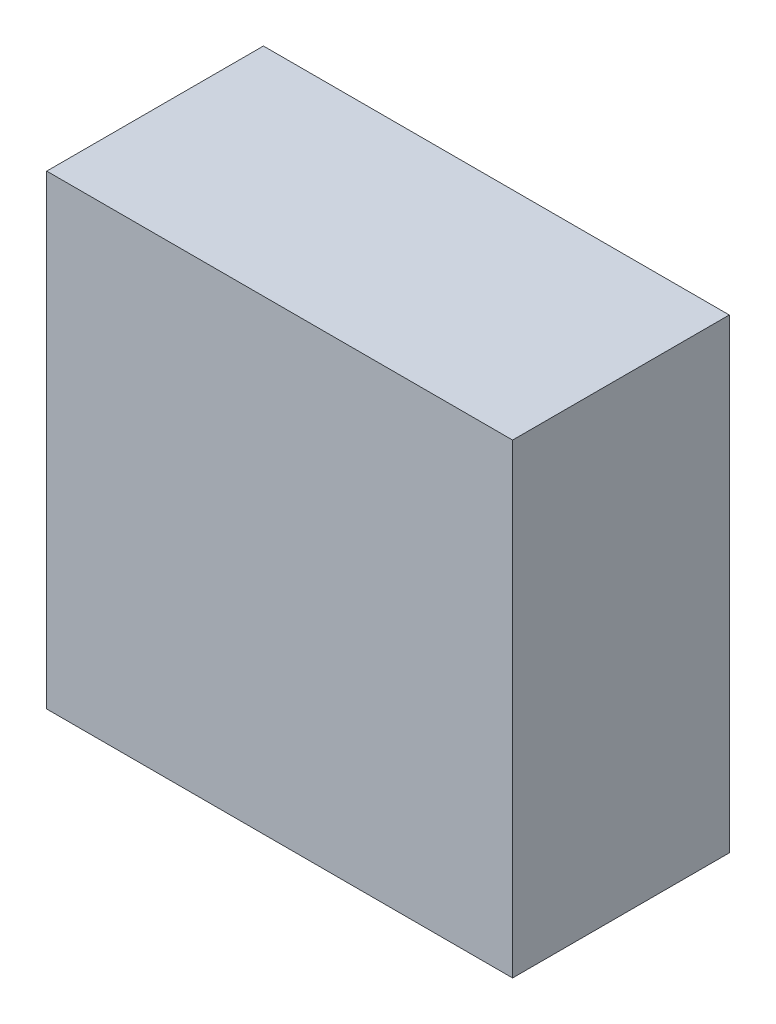
SolidWorks part; units mm, degrees
ref_plane "Plano frontal" through (0, 0, 0) normal (0, 0, 1) x (1, 0, 0)
ref_plane "Plano superior" through (0, 0, 0) normal (0, 1, 0) x (1, 0, 0)
ref_plane "Plano direito" through (0, 0, 0) normal (1, 0, 0) x (0, 0, -1)
other "Centro da massa"
sketch "Esboço1" plane through (0, 0, 0) normal (0, 0, 1) x (1, 0, 0)
  line L1 (21.5, -21.5) -> (-21.5, -21.5)
  line L2 (21.5, -21.5) -> (21.5, 21.5)
  line L3 (21.5, 21.5) -> (-21.5, 21.5)
  line L4 (-21.5, -21.5) -> (-21.5, 21.5)
  line L5 (21.5, -21.5) -> (-21.5, 21.5) construction
  line L6 (21.5, 21.5) -> (-21.5, -21.5) construction
  point P0 (0, 0)
  dimension "D1" = 43
  dimension "D2" = 43
extrude "Ressalto-extrusão1" add sketch "Esboço1" along normal blind 20
